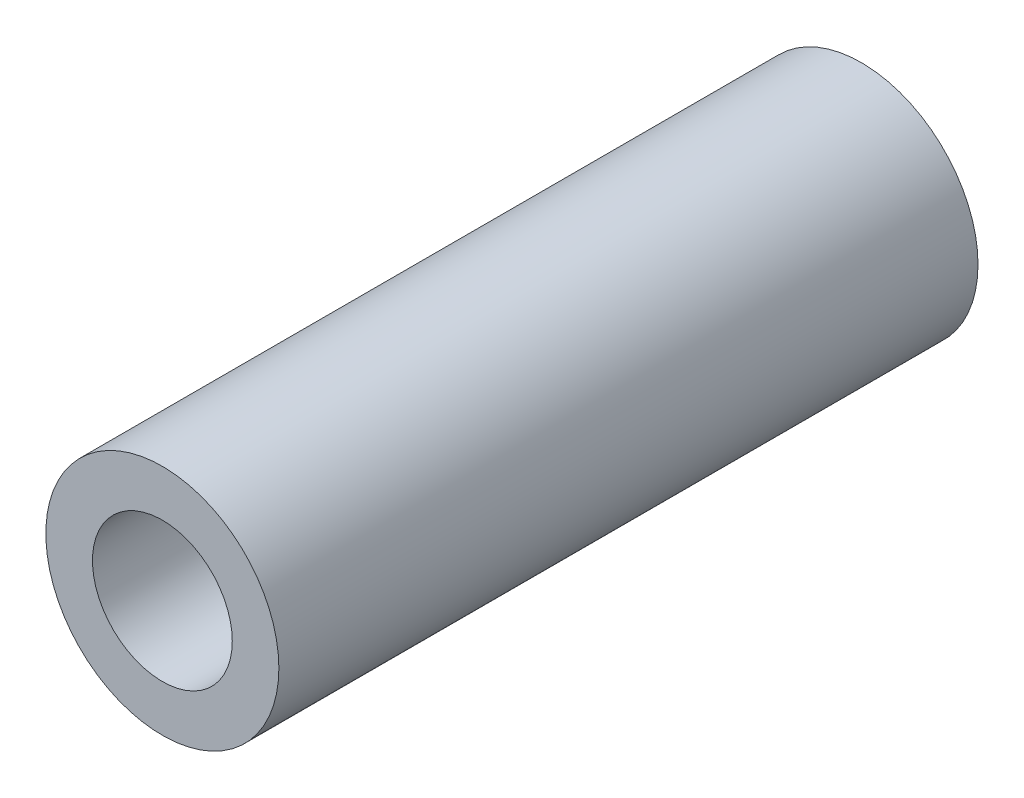
SolidWorks part; units mm, degrees
material "1060 合金"
ref_plane "前视基准面" through (0, 0, 0) normal (0, 0, 1) x (1, 0, 0)
ref_plane "上视基准面" through (0, 0, 0) normal (0, 1, 0) x (1, 0, 0)
ref_plane "右视基准面" through (0, 0, 0) normal (1, 0, 0) x (0, 0, -1)
other "Configuration Table"
sketch "草图1" plane through (0, 0, 0) normal (0, 0, 1) x (1, 0, 0)
  circle A0 centre (0, 0) radius 3
  circle A1 centre (0, 0) radius 5
  dimension "D1" = 6
  dimension "D2" = 10
extrude "凸台-拉伸1" add sketch "草图1" along normal blind 30
